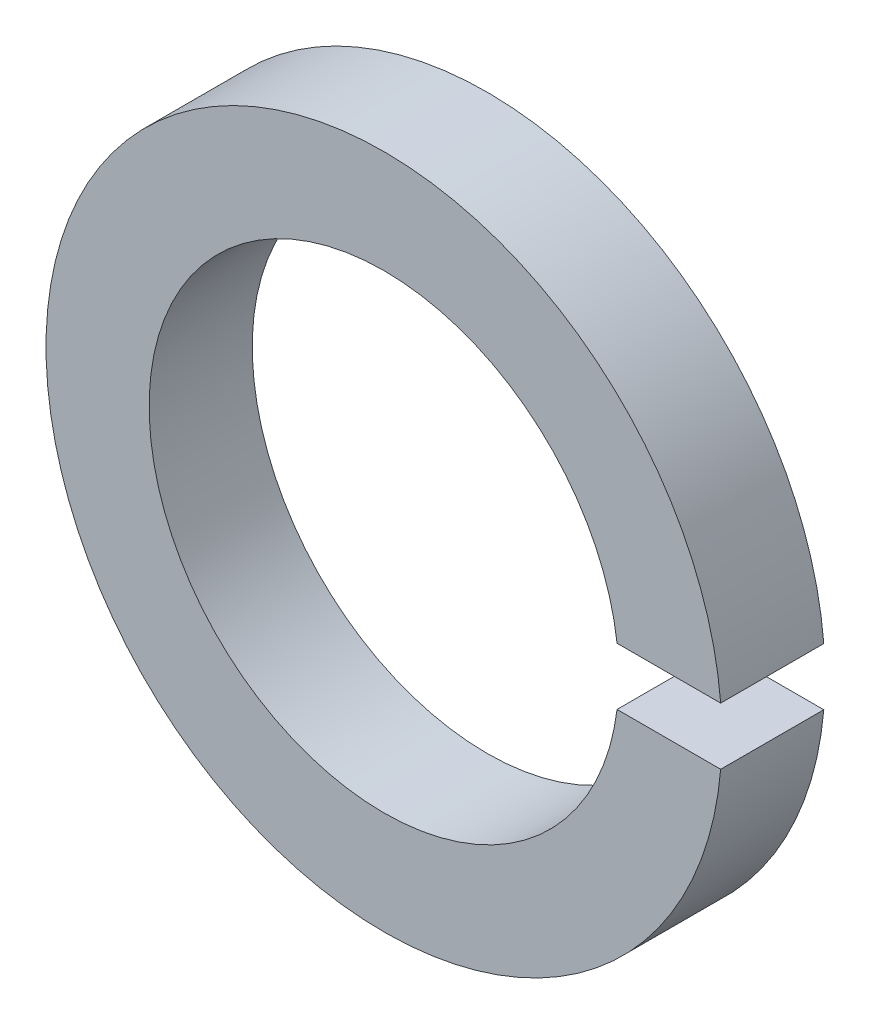
SolidWorks part; units mm, degrees
ref_plane "Спереди" through (0, 0, 0) normal (0, 0, 1) x (1, 0, 0)
ref_plane "Сверху" through (0, 0, 0) normal (0, 1, 0) x (1, 0, 0)
ref_plane "Справа" through (0, 0, 0) normal (1, 0, 0) x (0, 0, -1)
sketch "Эскиз1" plane through (0, 0, 0) normal (0, 0, 1) x (1, 0, 0)
  circle A0 centre (0, 0) radius 14.75
  circle A1 centre (0, 0) radius 10.25
  dimension "D1" = 4.5
  dimension "D2" = 20.5
extrude "Вытянуть1" add sketch "Эскиз1" along normal blind 4.5
sketch "Эскиз2" plane through (0, 0, 4.5) normal (0, 0, 1) x (1, 0, 0)
  line L0 (0, 0) -> (0.123, 0) construction
  line L3 (0, 1.25) -> (14.75, 1.25)
  line L4 (0, 1.25) -> (0, -1.25)
  line L5 (0, -1.25) -> (14.75, -1.25)
  line L6 (14.75, 1.25) -> (14.75, -1.25)
  circle A1 centre (0, 0) radius 14.75 construction
  dimension "D2" = 2.5
extrude "Вырез-Вытянуть1" cut sketch "Эскиз2" against normal through all
